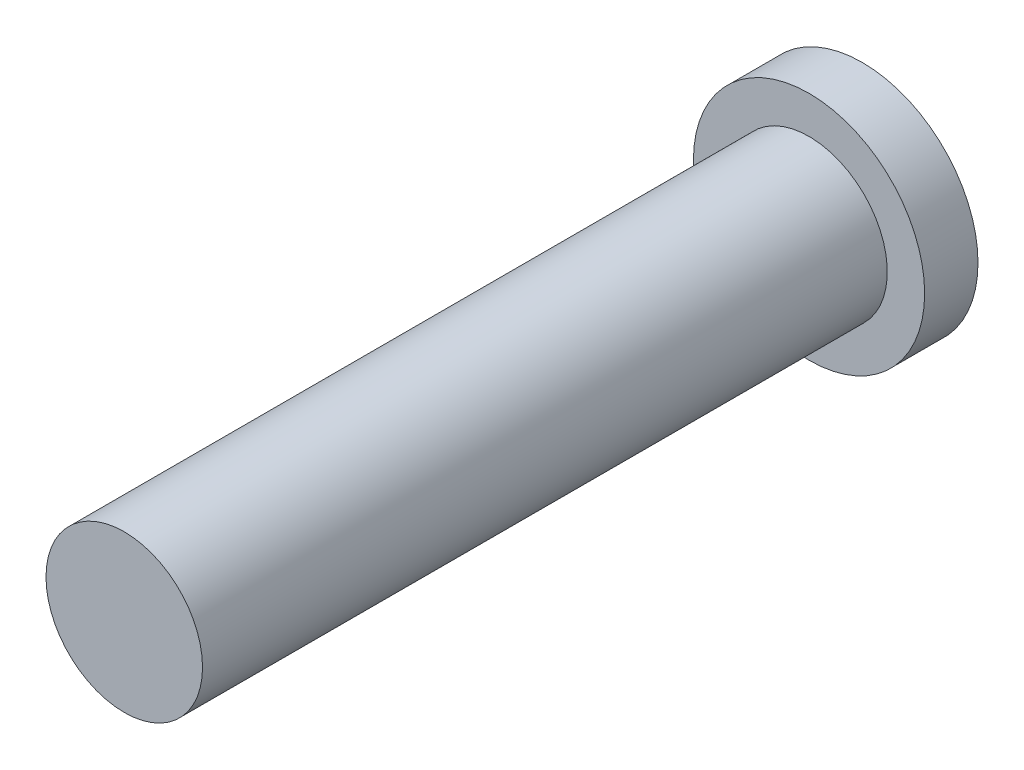
SolidWorks part; units mm, degrees
ref_plane "Front Plane" through (0, 0, 0) normal (0, 0, 1) x (1, 0, 0)
ref_plane "Top Plane" through (0, 0, 0) normal (0, 1, 0) x (1, 0, 0)
ref_plane "Right Plane" through (0, 0, 0) normal (1, 0, 0) x (0, 0, -1)
sketch "Sketch1" plane through (0, 0, 0) normal (0, 0, 1) x (1, 0, 0)
  circle A0 centre (0, 0) radius 4.4
  dimension "D1" = 8.8
extrude "Boss-Extrude1" add sketch "Sketch1" along normal blind 41.5
sketch "Sketch2" plane through (0, 0, 0) normal (0, 0, -1) x (-1, 0, 0)
  circle A0 centre (0, 0) radius 6.5
  dimension "D1" = 13
extrude "Boss-Extrude2" add sketch "Sketch2" against normal blind 3
